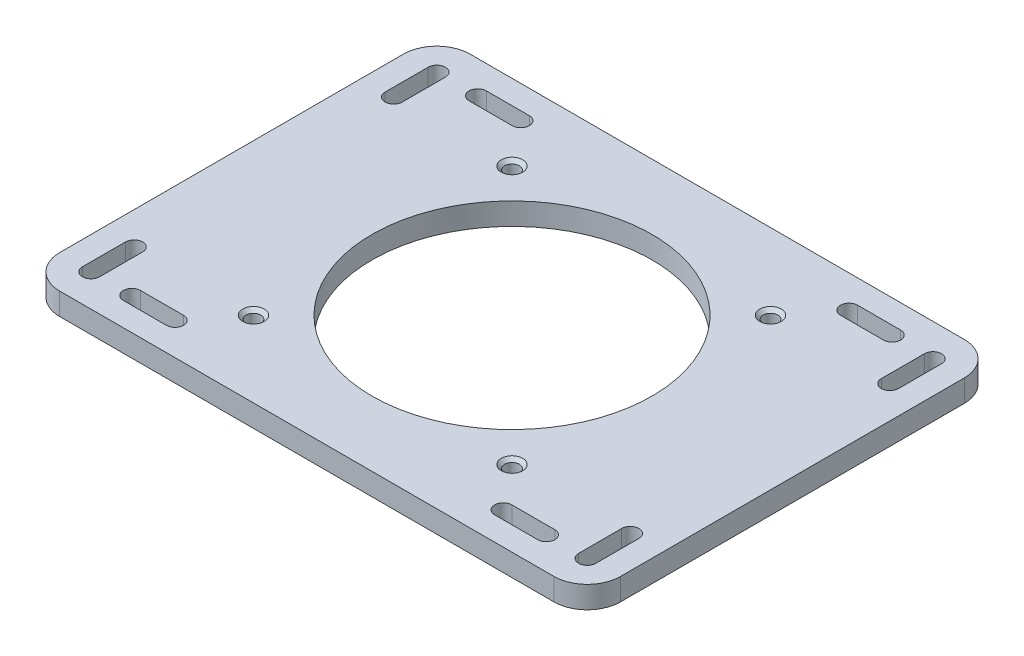
SolidWorks part; units mm, degrees
ref_plane "Front Plane" through (0, 0, 0) normal (0, 0, 1) x (1, 0, 0)
ref_plane "Top Plane" through (0, 0, 0) normal (0, 1, 0) x (1, 0, 0)
ref_plane "Right Plane" through (0, 0, 0) normal (1, 0, 0) x (0, 0, -1)
sketch "Sketch1" plane through (0, 0, 0) normal (0, 1, 0) x (1, 0, 0)
  line L1 (0, 0) -> (260.35, 0)
  line L2 (0, 0) -> (0, 190.5)
  line L3 (0, 190.5) -> (260.35, 190.5)
  line L4 (260.35, 0) -> (260.35, 190.5)
  dimension "D1" = 260.35
  dimension "D2" = 190.5
extrude "Base" add sketch "Sketch1" along normal blind 10.25
sketch "Sketch2" plane through (0, 10.25, 0) normal (0, 1, 0) x (1, 0, 0)
  line L0 (260.35, 190.5) -> (0, 190.5) construction
  line L3 (260.35, 0) -> (260.35, 190.5) construction
  line L7 (206.35, 15) -> (226.35, 15) construction
  line L12 (0, 0) -> (260.35, 0) construction
  line L13 (206.35, 19) -> (226.35, 19)
  line L14 (0, 190.5) -> (0, 0) construction
  line L15 (245.35, 15) -> (245.35, 35) construction
  line L16 (241.35, 15) -> (241.35, 35)
  line L17 (249.35, 15) -> (249.35, 35)
  line L18 (15, 15) -> (15, 35) construction
  line L19 (11, 15) -> (11, 35)
  line L20 (19, 15) -> (19, 35)
  line L21 (15, 155.5) -> (15, 175.5) construction
  line L22 (11, 155.5) -> (11, 175.5)
  line L23 (19, 155.5) -> (19, 175.5)
  line L24 (245.35, 155.5) -> (245.35, 175.5) construction
  line L25 (241.35, 155.5) -> (241.35, 175.5)
  line L26 (249.35, 155.5) -> (249.35, 175.5)
  line L27 (34, 15) -> (54, 15) construction
  line L28 (34, 19) -> (54, 19)
  line L29 (34, 11) -> (54, 11)
  line L30 (206.35, 11) -> (226.35, 11)
  line L31 (206.35, 175.5) -> (226.35, 175.5) construction
  line L32 (206.35, 179.5) -> (226.35, 179.5)
  line L33 (206.35, 171.5) -> (226.35, 171.5)
  line L34 (34, 175.5) -> (54, 175.5) construction
  line L35 (34, 179.5) -> (54, 179.5)
  line L36 (34, 171.5) -> (54, 171.5)
  circle A0 centre (130.175, 95.25) radius 65
  arc A1 (241.35, 15) -> (249.35, 15) centre (245.35, 15) ccw
  arc A2 (249.35, 35) -> (241.35, 35) centre (245.35, 35) ccw
  arc A3 (11, 15) -> (19, 15) centre (15, 15) ccw
  arc A4 (19, 35) -> (11, 35) centre (15, 35) ccw
  arc A5 (11, 155.5) -> (19, 155.5) centre (15, 155.5) ccw
  arc A6 (19, 175.5) -> (11, 175.5) centre (15, 175.5) ccw
  arc A7 (241.35, 155.5) -> (249.35, 155.5) centre (245.35, 155.5) ccw
  arc A8 (249.35, 175.5) -> (241.35, 175.5) centre (245.35, 175.5) ccw
  arc A9 (34, 19) -> (34, 11) centre (34, 15) ccw
  arc A10 (54, 11) -> (54, 19) centre (54, 15) ccw
  arc A11 (206.35, 19) -> (206.35, 11) centre (206.35, 15) ccw
  arc A12 (226.35, 11) -> (226.35, 19) centre (226.35, 15) ccw
  arc A13 (206.35, 179.5) -> (206.35, 171.5) centre (206.35, 175.5) ccw
  arc A14 (226.35, 171.5) -> (226.35, 179.5) centre (226.35, 175.5) ccw
  arc A15 (34, 179.5) -> (34, 171.5) centre (34, 175.5) ccw
  arc A16 (54, 171.5) -> (54, 179.5) centre (54, 175.5) ccw
  point P17 (245.35, 25)
  point P27 (15, 25)
  point P34 (15, 165.5)
  point P41 (245.35, 165.5)
  point P46 (44, 15)
  point P52 (216.35, 15)
  point P59 (216.35, 175.5)
  point P66 (44, 175.5)
  dimension "D1" = 130
  dimension "D8" = 20
  dimension "D9" = 15
  dimension "D2" = 95.25
  dimension "D3" = 130.175
  dimension "D4" = 2
  dimension "D5" = 2
  dimension "D6" = 8
  dimension "D7" = 11
  dimension "D12" = 15
  dimension "D13" = 15
  dimension "D14" = 15
  dimension "D15" = 34
  dimension "D16" = 20
  dimension "D17" = 8
  dimension "D18" = 34
  dimension "D19" = 15
  dimension "D20" = 34
  dimension "D10" = 2
  dimension "D11" = 2
extrude "Holes" cut sketch "Sketch2" against normal through all
sketch "Sketch6" plane through (0, 10.25, 0) normal (0, 1, 0) x (1, 0, 0)
  line L0 (260.35, 190.5) -> (0, 190.5) construction
  line L2 (0, 190.5) -> (0, 0) construction
  line L4 (260.35, 0) -> (260.35, 190.5) construction
  point P0 (70.175, 155.25)
  point P2 (190.175, 155.25)
  point P4 (190.175, 35.25)
  point P6 (70.175, 35.25)
  point P17 (34.4913, 31.8806)
  point P18 (0, 0)
  point P21 (0, 0)
  point P22 (0, 0)
  point P27 (118.844, 115.3939)
  point P30 (0, 0)
  point P31 (0, 0)
  dimension "D1" = 35.25
  dimension "D2" = 120
  dimension "D3" = 120
  dimension "D4" = 70.175
  dimension "D5" = 70.175
hole_wizard "M8 Arm Mount Holes" positions "Sketch6" profile "Sketch7" hole size "M8x1.25" standard "ANSI Metric" end condition through all
sketch "Sketch7" plane through (70.175, 10.25, -155.25) normal (1, 0, 0) x (0, 0, 1)
  line L0 (0, 0) -> (0, 10.25)
  line L1 (0, 10.25) -> (3.4, 10.25)
  line L2 (3.4, 10.25) -> (3.4, 1.6)
  line L3 (3.4, 1.6) -> (5, 0)
  line L5 (5, 0) -> (0, 0)
  line L6 (-3.4, 1.6) -> (-5, 0) construction
  line L11 (0, -6.35) -> (0, 107.95) construction
  dimension "Thru Hole Dia." = 6.8
  dimension "Thru Hole Depth" = 10.25
  dimension "Near C'Sink Dia." = 10
  dimension "Near C'Sink Angle" = 90
fillet "Fillet1" radius 15.5 4 edges at (0, 5.125, -190.5) (0, 5.125, 0) (260.35, 5.125, 0) (260.35, 5.125, -190.5)
